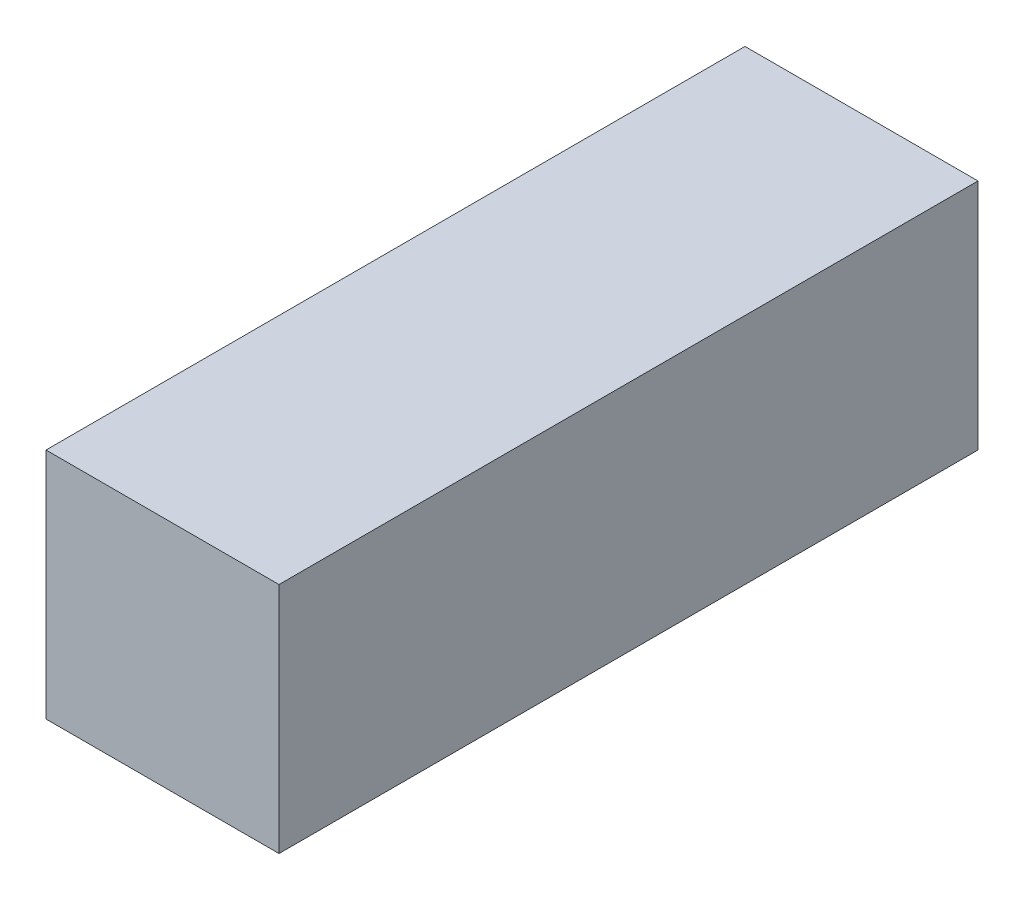
SolidWorks part; units mm, degrees
ref_plane "Front Plane" through (0, 0, 0) normal (0, 0, 1) x (1, 0, 0)
ref_plane "Top Plane" through (0, 0, 0) normal (0, 1, 0) x (1, 0, 0)
ref_plane "Right Plane" through (0, 0, 0) normal (1, 0, 0) x (0, 0, -1)
sketch "Sketch1" plane through (0, 0, 0) normal (0, 0, 1) x (1, 0, 0)
  line L1 (-57.7617, 42.5993) -> (42.2383, 42.5993)
  line L2 (-57.7617, 42.5993) -> (-57.7617, -57.4007)
  line L3 (-57.7617, -57.4007) -> (42.2383, -57.4007)
  line L4 (42.2383, 42.5993) -> (42.2383, -57.4007)
  dimension "D1" = 100
  dimension "D2" = 100
extrude "Boss-Extrude1" add sketch "Sketch1" along normal blind 300
